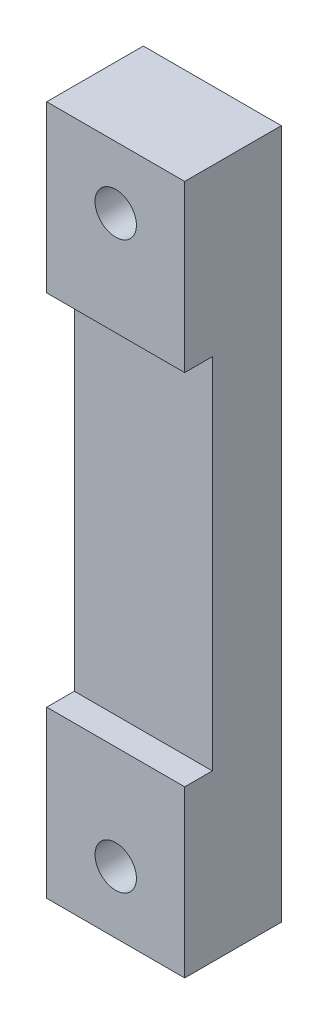
SolidWorks part; units mm, degrees
ref_plane "Plan de face" through (0, 0, 0) normal (0, 0, 1) x (1, 0, 0)
ref_plane "Plan de dessus" through (0, 0, 0) normal (0, 1, 0) x (1, 0, 0)
ref_plane "Plan de droite" through (0, 0, 0) normal (1, 0, 0) x (0, 0, -1)
sketch "Esquisse1" plane through (0, 0, 0) normal (0, 0, 1) x (1, 0, 0)
  line L4 (-23.9613, 25.7996) -> (-23.9613, -24.2004)
  line L5 (-23.9613, -24.2004) -> (-13.9613, -24.2004)
  line L6 (-13.9613, -24.2004) -> (-13.9613, 25.7996)
  line L7 (-13.9613, 25.7996) -> (-23.9613, 25.7996)
  dimension "D1" = 50
  dimension "D2" = 10
extrude "Boss.-Extru.1" add sketch "Esquisse1" along normal blind 5
sketch "Esquisse4" plane through (0, 0, 5) normal (0, 0, 1) x (1, 0, 0)
  line L0 (-23.9613, 25.7996) -> (-13.9613, 25.7996)
  line L1 (-13.9613, 25.7996) -> (-13.9613, 13.7996)
  line L2 (-13.9613, -24.2004) -> (-13.9613, 25.7996) construction
  line L3 (-13.9613, 13.7996) -> (-23.9613, 13.7996)
  line L4 (-23.9613, 25.7996) -> (-23.9613, -24.2004) construction
  line L5 (-23.9613, 13.7996) -> (-23.9613, 25.7996)
  dimension "D1" = 12
extrude "Boss.-Extru.2" add sketch "Esquisse4" along normal blind 2
sketch "Esquisse5" plane through (0, 0, 5) normal (0, 0, 1) x (1, 0, 0)
  line L1 (-23.9613, -24.2004) -> (-13.9613, -24.2004)
  line L2 (-13.9613, -24.2004) -> (-13.9613, -12.2004)
  line L3 (-13.9613, -24.2004) -> (-13.9613, 13.7996) construction
  line L4 (-13.9613, -12.2004) -> (-23.9613, -12.2004)
  line L5 (-23.9613, 13.7996) -> (-23.9613, -24.2004) construction
  line L6 (-23.9613, -12.2004) -> (-23.9613, -24.2004)
  dimension "D1" = 12
extrude "Boss.-Extru.3" add sketch "Esquisse5" along normal blind 2 contours L6 L1 L2 L4
sketch "Esquisse7" plane through (0, 0, 7) normal (0, 0, 1) x (1, 0, 0)
  line L1 (-13.9613, -24.2004) -> (-18.9613, -24.2004)
  line L2 (-13.9613, -24.2004) -> (-13.9613, -19.7004)
  line L3 (-13.9613, -19.7004) -> (-18.9613, -19.7004)
  line L4 (-18.9613, -24.2004) -> (-18.9613, -19.7004)
  circle A0 centre (-18.9613, -19.7004) radius 1.5
  dimension "D1" = 3
  dimension "D2" = 4.5
  dimension "D3" = 5
extrude "Enlèv. mat.-Extru.2" cut sketch "Esquisse7" against normal blind 23.0739 contours A0
sketch "Esquisse8" plane through (0, 0, 7) normal (0, 0, 1) x (1, 0, 0)
  line L1 (-13.9613, 25.7996) -> (-18.9613, 25.7996)
  line L2 (-13.9613, 25.7996) -> (-13.9613, 21.2996)
  line L3 (-13.9613, 21.2996) -> (-18.9613, 21.2996)
  line L4 (-18.9613, 25.7996) -> (-18.9613, 21.2996)
  circle A0 centre (-18.9613, 21.2996) radius 1.5
  point P2 (0, 0)
  dimension "D1" = 3
  dimension "D2" = 4.5
  dimension "D3" = 5
extrude "Enlèv. mat.-Extru.3" cut sketch "Esquisse8" against normal blind 23.0739 contours A0
